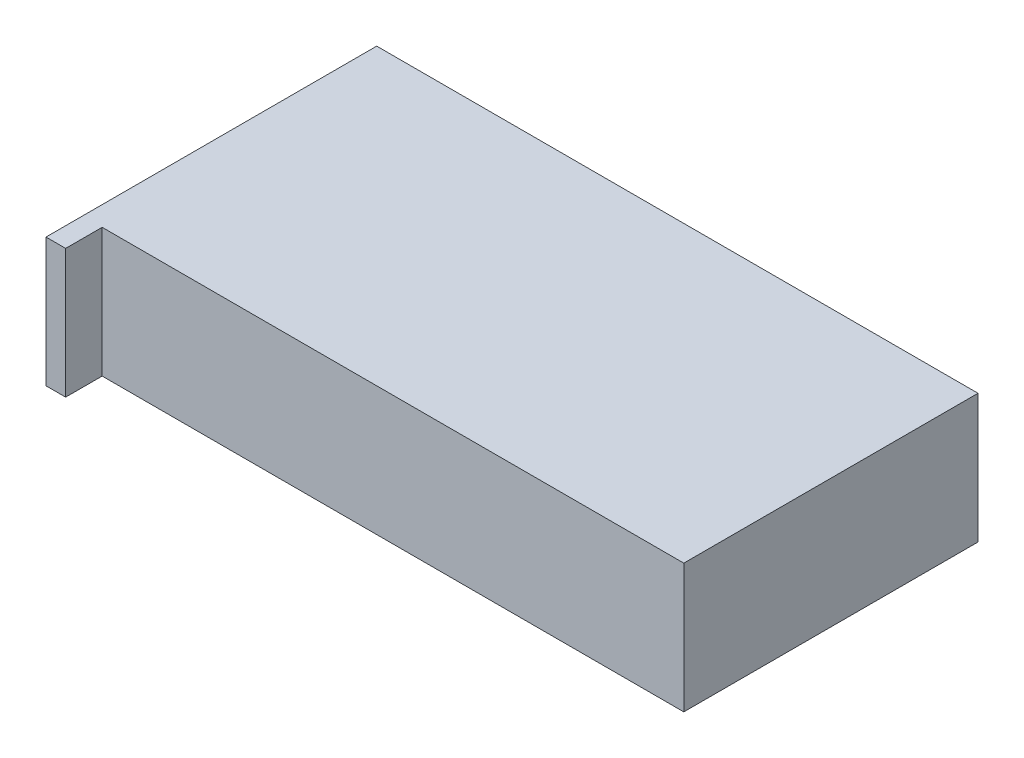
SolidWorks part; units mm, degrees
ref_plane "Front Plane" through (0, 0, 0) normal (0, 0, 1) x (1, 0, 0)
ref_plane "Top Plane" through (0, 0, 0) normal (0, 1, 0) x (1, 0, 0)
ref_plane "Right Plane" through (0, 0, 0) normal (1, 0, 0) x (0, 0, -1)
sketch "Sketch1" plane through (0, 0, 0) normal (0, 1, 0) x (1, 0, 0)
  line L1 (0, 0) -> (71.12, 0)
  line L2 (0, 0) -> (0, 34.798)
  line L3 (0, 34.798) -> (71.12, 34.798)
  line L4 (71.12, 0) -> (71.12, 34.798)
  dimension "D1" = 71.12
  dimension "D2" = 34.798
extrude "Boss-Extrude1" add sketch "Sketch1" along normal blind 15.24
sketch "Sketch2" plane through (0, 0, 0) normal (0, 0, 1) x (1, 0, 0)
  line L0 (0, 0) -> (71.12, 0) construction
  line L1 (0, 15.24) -> (2.3243, 15.24)
  line L2 (0, 15.24) -> (0, 0)
  line L3 (0, 0) -> (2.3243, 0)
  line L4 (2.3243, 15.24) -> (2.3243, 0)
extrude "Boss-Extrude2" add sketch "Sketch2" along normal blind 4.318
